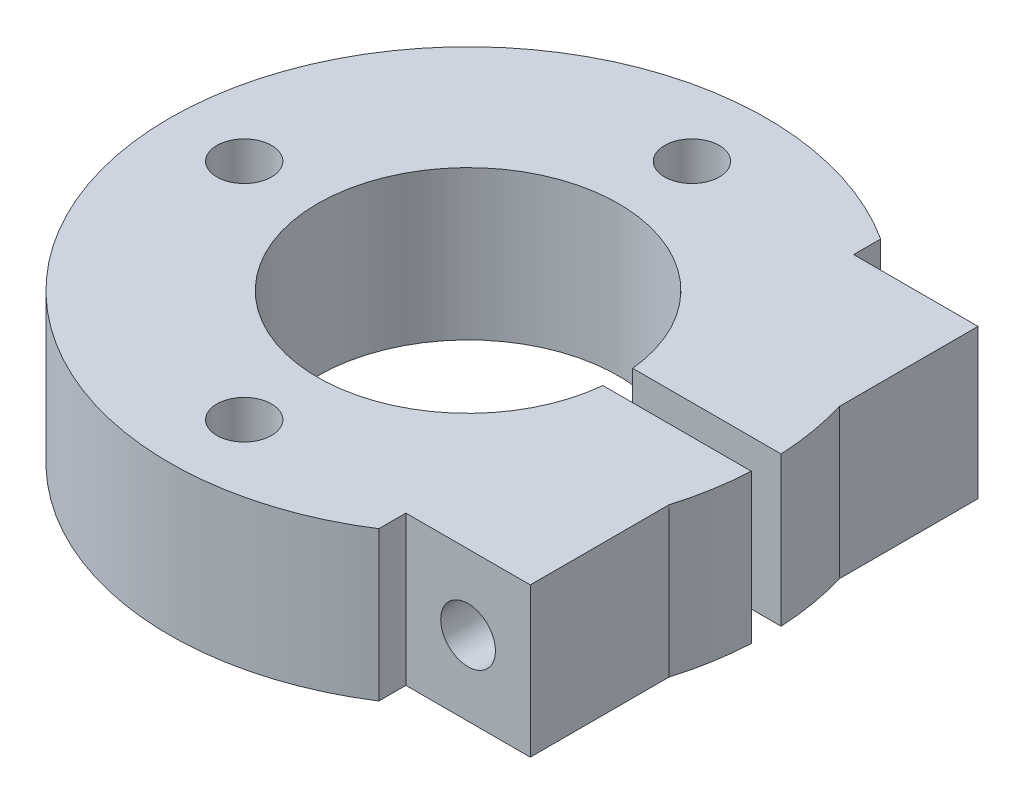
SolidWorks part; units mm, degrees
other "Pivot Shaft Split Clamp Collar"
ref_plane "Front Plane" through (0, 0, 0) normal (0, 0, 1) x (1, 0, 0)
ref_plane "Top Plane" through (0, 0, 0) normal (0, 1, 0) x (1, 0, 0)
ref_plane "Right Plane" through (0, 0, 0) normal (1, 0, 0) x (0, 0, -1)
sketch3d "Main Profile Sketch datum points"
  point P0 (0, -157, 0)
  point P1 (10, -157, 0)
  point P2 (0, -157, 10)
ref_plane "Main Profile Sketch plane" through (0, -157, 0) normal (0, -1, 0) x (-1, 0, 0)
sketch "Main Profile Sketch" plane through (0, -157, 0) normal (0, -1, 0) x (-1, 0, 0)
  line L0 (44.7917, -3.4278) -> (44.7917, -9)
  line L1 (44.7917, -9) -> (49.7917, -9)
  line L2 (49.7917, -9) -> (49.7917, -10.0871)
  line L3 (49.7917, 10.0871) -> (49.7917, 9)
  line L4 (44.7917, 9) -> (49.7917, 9)
  line L5 (44.7917, 9) -> (44.7917, 3.4278)
  line L6 (44.3067, 0.6) -> (50.2715, 0.6)
  line L7 (44.3067, -0.6) -> (50.2715, -0.6)
  arc A0 (44.3067, -0.6) -> (44.7917, -3.4278) centre (56.2917, 0) ccw
  arc A1 (49.7917, -10.0871) -> (49.7917, 10.0871) centre (56.2917, 0) ccw
  arc A2 (44.7917, 3.4278) -> (44.3067, 0.6) centre (56.2917, 0) ccw
  arc A3 (50.2715, -0.6) -> (50.2715, 0.6) centre (56.2917, 0) ccw
  circle A4 centre (65.2917, 0) radius 1.1
  circle A5 centre (56.2917, 9) radius 1.1
  circle A6 centre (56.2917, -9) radius 1.1
extrude "Main Extrusion" add sketch "Main Profile Sketch" along normal blind 4 separate body
sketch3d "Detail Profile 2 Sketch datum points"
  point P0 (0, -161, 0)
  point P1 (10, -161, 0)
  point P2 (0, -161, 10)
ref_plane "Detail Profile 2 Sketch plane" through (0, -161, 0) normal (0, -1, 0) x (-1, 0, 0)
sketch "Detail Profile 2 Sketch" plane through (0, -161, 0) normal (0, -1, 0) x (-1, 0, 0)
  line L0 (44.7917, -3.4278) -> (44.7917, -9)
  line L1 (44.7917, -9) -> (49.7917, -9)
  line L2 (49.7917, -9) -> (49.7917, -10.0871)
  line L3 (49.7917, 10.0871) -> (49.7917, 9)
  line L4 (44.7917, 9) -> (49.7917, 9)
  line L5 (44.7917, 9) -> (44.7917, 3.4278)
  line L6 (44.3067, 0.6) -> (50.2715, 0.6)
  line L7 (44.3067, -0.6) -> (50.2715, -0.6)
  arc A0 (44.3067, -0.6) -> (44.7917, -3.4278) centre (56.2917, 0) ccw
  arc A1 (49.7917, -10.0871) -> (49.7917, 10.0871) centre (56.2917, 0) ccw
  arc A2 (44.7917, 3.4278) -> (44.3067, 0.6) centre (56.2917, 0) ccw
  arc A3 (50.2715, -0.6) -> (50.2715, 0.6) centre (56.2917, 0) ccw
  circle A4 centre (65.2917, 0) radius 2
  circle A5 centre (56.2917, 9) radius 2
  circle A6 centre (56.2917, -9) radius 2
extrude "Detail Extrusion 2" add sketch "Detail Profile 2 Sketch" along normal blind 2
sketch3d "Cross Bolt Clearance profile datum points"
  point P0 (-47.2917, -160, -12)
  point P1 (-37.2917, -160, -12)
  point P2 (-47.2917, -150, -12)
ref_plane "Cross Bolt Clearance profile plane" through (0, 0, -12) normal (0, 0, 1) x (1, 0, 0)
sketch "Cross Bolt Clearance profile" plane through (0, 0, -12) normal (0, 0, 1) x (1, 0, 0)
  circle A0 centre (-47.2917, -160) radius 1.1
extrude "Cross Bolt Clearance" cut sketch "Cross Bolt Clearance profile" along normal blind 24
